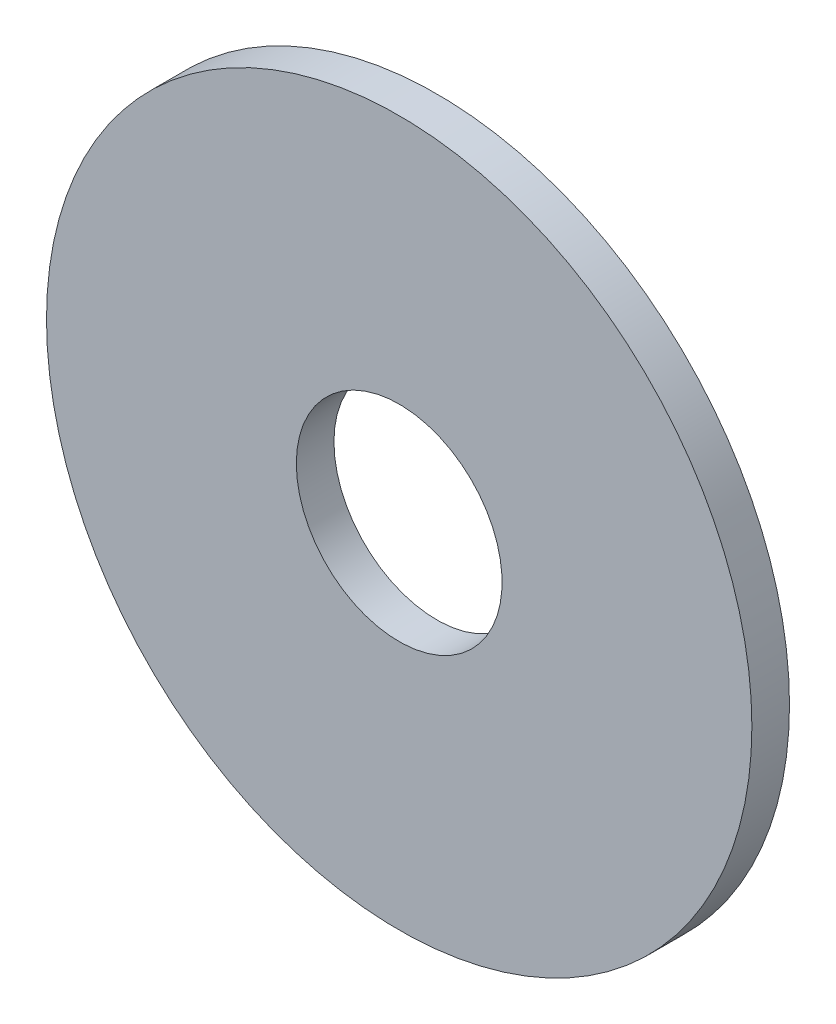
SolidWorks part; units mm, degrees
ref_plane "Front Plane" through (0, 0, 0) normal (0, 0, 1) x (1, 0, 0)
ref_plane "Top Plane" through (0, 0, 0) normal (0, 1, 0) x (1, 0, 0)
ref_plane "Right Plane" through (0, 0, 0) normal (1, 0, 0) x (0, 0, -1)
sketch "Sketch1" plane through (0, 0, 0) normal (1, 0, 0) x (0, 0, -1)
  line L0 (0, 0) -> (0, 19.05)
  line L1 (0, 5.5562) -> (-2.032, 5.5562)
  line L2 (-2.032, 5.5562) -> (-2.032, 19.05)
  line L3 (-2.032, 19.05) -> (0, 19.05)
  line L4 (0, 0) -> (-14.2664, 0) construction
  dimension "D1" = 19.05
  dimension "D2" = 5.5562
  dimension "D3" = 2.032
revolve "Revolve1" add sketch "Sketch1" angle 360 about L4
